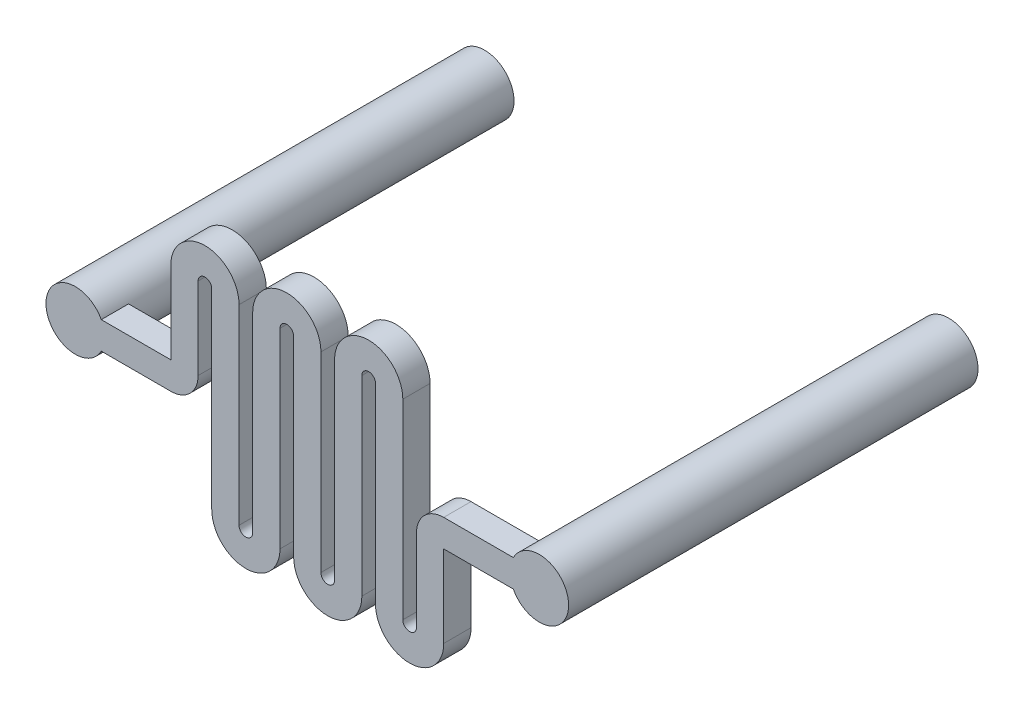
SolidWorks part; units mm, degrees
ref_plane "Front Plane" through (0, 0, 0) normal (0, 0, 1) x (1, 0, 0)
ref_plane "Top Plane" through (0, 0, 0) normal (0, 1, 0) x (1, 0, 0)
ref_plane "Right Plane" through (0, 0, 0) normal (1, 0, 0) x (0, 0, -1)
sketch "Sketch2" plane through (0, 0, 0) normal (0, 0, 1) x (1, 0, 0)
  line L3 (-20.5, -1) -> (-13.5, -1)
  line L6 (-11.5, 1) -> (-11.5, 7)
  line L9 (-10.5, 7) -> (-10.5, 0)
  line L12 (-10.5, 0) -> (-10.5, -7)
  line L15 (-5.5, -7) -> (-5.5, 0)
  line L18 (-5.5, 0) -> (-5.5, 7)
  line L21 (-4.5, 7) -> (-4.5, 0)
  line L22 (-4.5, 0) -> (-4.5, -7)
  line L23 (0.5, -7) -> (0.5, 0)
  line L24 (0.5, 0) -> (0.5, 7)
  line L25 (1.5, 7) -> (1.5, 0)
  line L26 (1.5, 0) -> (1.5, -7)
  line L27 (6.5, -7) -> (6.5, -1)
  line L28 (6.5, -1) -> (13.5, -1)
  line L29 (-20.5, 1) -> (-13.5, 1)
  line L30 (-13.5, 1) -> (-13.5, 7)
  line L31 (-8.5, 7) -> (-8.5, 0)
  line L32 (-8.5, 0) -> (-8.5, -7)
  line L33 (-7.5, -7) -> (-7.5, 0)
  line L34 (-7.5, 0) -> (-7.5, 7)
  line L35 (-2.5, 7) -> (-2.5, 0)
  line L36 (-2.5, 0) -> (-2.5, -7)
  line L37 (-1.5, -7) -> (-1.5, 0)
  line L38 (-1.5, 0) -> (-1.5, 7)
  line L39 (3.5, 7) -> (3.5, 0)
  line L40 (3.5, 0) -> (3.5, -7)
  line L41 (4.5, -7) -> (4.5, -1)
  line L42 (6.5, 1) -> (13.5, 1)
  arc A8 (-11.5, 1) -> (-13.5, -1) centre (-13.5, 1) cw
  arc A9 (-11.5, 7) -> (-10.5, 7) centre (-11, 7) cw
  arc A10 (-10.5, -7) -> (-5.5, -7) centre (-8, -7) ccw
  arc A11 (-5.5, 7) -> (-4.5, 7) centre (-5, 7) cw
  arc A12 (-4.5, -7) -> (0.5, -7) centre (-2, -7) ccw
  arc A13 (0.5, 7) -> (1.5, 7) centre (1, 7) cw
  arc A14 (1.5, -7) -> (6.5, -7) centre (4, -7) ccw
  arc A17 (-13.5, 7) -> (-8.5, 7) centre (-11, 7) cw
  arc A18 (-8.5, -7) -> (-7.5, -7) centre (-8, -7) ccw
  arc A19 (-7.5, 7) -> (-2.5, 7) centre (-5, 7) cw
  arc A20 (-2.5, -7) -> (-1.5, -7) centre (-2, -7) ccw
  arc A21 (-1.5, 7) -> (3.5, 7) centre (1, 7) cw
  arc A22 (3.5, -7) -> (4.5, -7) centre (4, -7) ccw
  arc A23 (4.5, -1) -> (6.5, 1) centre (6.5, -1) cw
  arc A24 (-20.5, 1) -> (-20.5, -1) centre (-20.5, 0) ccw
  arc A25 (13.5, -1) -> (13.5, 1) centre (13.5, 0) ccw
  point P4 (0, 0)
  point P32 (5.5, 0)
  point P35 (-12.5, 0)
  dimension "D1" = 8
  dimension "D14" = 8
extrude "Boss-Extrude1" add sketch "Sketch2" along normal blind 2
ref_plane "Plane1" through (0, 0, 0) normal (0, 1, 0) x (1, 0, 0)
sketch "Sketch3" plane through (0, 0, 0) normal (0, 1, 0) x (1, 0, 0)
  line L1 (-20.5, 28) -> (-22.65, 28)
  line L2 (-20.5, -2) -> (-20.5, 28)
  line L6 (-22.65, 28) -> (-22.65, -2)
  line L7 (-22.65, -2) -> (-20.5, -2)
  dimension "D1" = 2.15
  dimension "D3" = 30
ref_plane "Plane2" through (0, 0, 0) normal (0, 1, 0) x (1, 0, 0)
sketch "Sketch4" plane through (0, 0, 0) normal (0, 1, 0) x (1, 0, 0)
  line L1 (13.5, 28) -> (15.65, 28)
  line L2 (13.5, -2) -> (13.5, 28)
  line L6 (15.65, 28) -> (15.65, -2)
  line L7 (15.65, -2) -> (13.5, -2)
  dimension "D1" = 2.15
  dimension "D3" = 30
revolve "Revolve1" add sketch "Sketch3" angle 360 about L2
revolve "Revolve2" add sketch "Sketch4" angle 360 about L2
sketch "Sketch6" plane through (0, 0, -28) normal (0, 0, -1) x (-1, 0, 0)
  circle A0 centre (-13.5, 0) radius 1.5
  circle A1 centre (20.5, 0) radius 1.5
  dimension "D1" = 3
  dimension "D2" = 3
extrude "Cut-Extrude1" cut sketch "Sketch6" against normal blind 29
